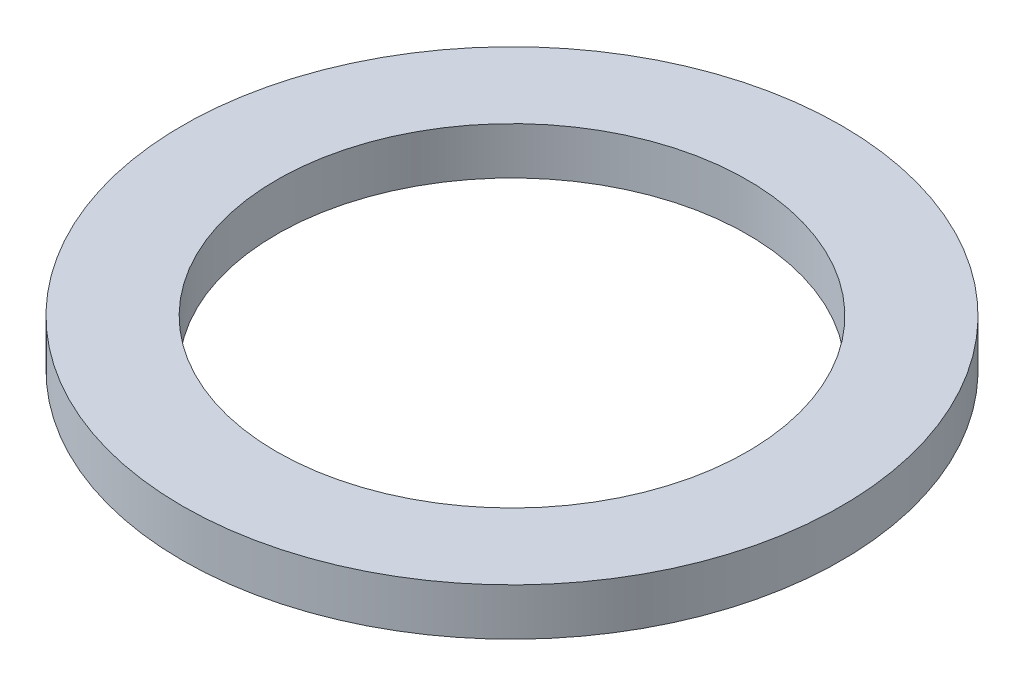
SolidWorks part; units mm, degrees
material "1.4000 (X6Cr13)"
ref_plane "前视基准面" through (0, 0, 0) normal (0, 0, 1) x (1, 0, 0)
ref_plane "上视基准面" through (0, 0, 0) normal (0, 1, 0) x (1, 0, 0)
ref_plane "右视基准面" through (0, 0, 0) normal (1, 0, 0) x (0, 0, -1)
sketch "草图1" plane through (0, 0, 0) normal (0, 1, 0) x (1, 0, 0)
  circle A0 centre (0, 0) radius 2.5
  circle A1 centre (0, 0) radius 3.5
  dimension "D1" = 5
  dimension "D2" = 7
extrude "凸台-拉伸1" add sketch "草图1" along normal blind 0.5
